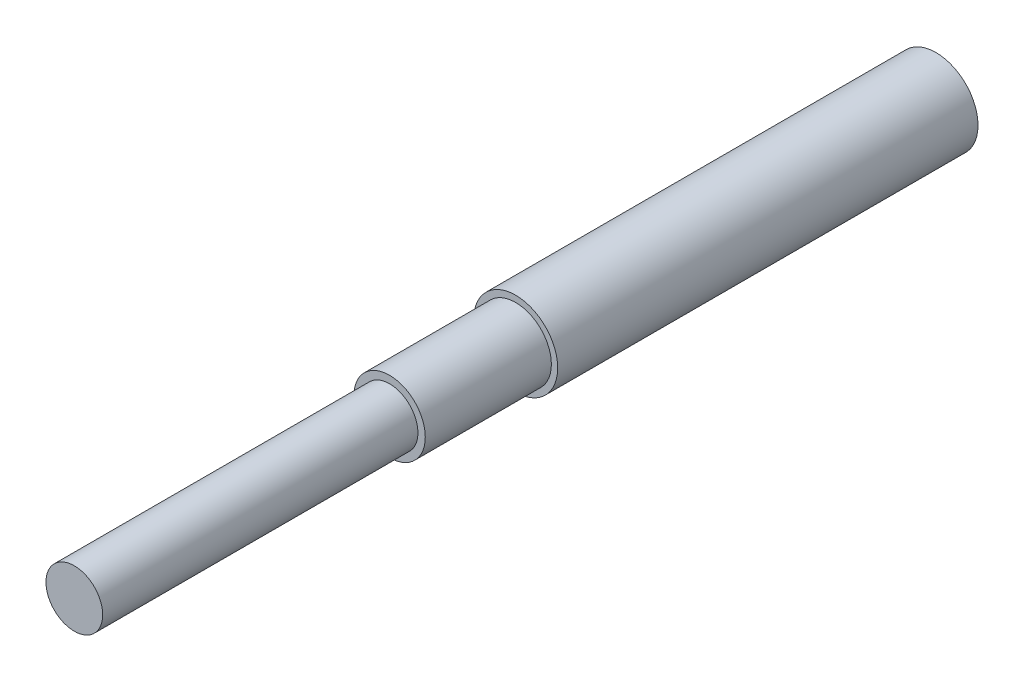
SolidWorks part; units mm, degrees
ref_plane "Plan de face" through (0, 0, 0) normal (0, 0, 1) x (1, 0, 0)
ref_plane "Plan de dessus" through (0, 0, 0) normal (0, 1, 0) x (1, 0, 0)
ref_plane "Plan de droite" through (0, 0, 0) normal (1, 0, 0) x (0, 0, -1)
sketch "Esquisse1" plane through (0, 0, 0) normal (0, 0, 1) x (1, 0, 0)
  circle A0 centre (0, 0) radius 2
  dimension "D1" = 4
extrude "Boss.-Extru.1" add sketch "Esquisse1" along normal blind 20
sketch "Esquisse8" plane through (0, 0, 20) normal (0, 0, 1) x (1, 0, 0)
  circle A0 centre (0, 0) radius 1.7
  dimension "D1" = 3.4
extrude "Boss.-Extru.2" add sketch "Esquisse8" along normal blind 6
sketch "Esquisse9" plane through (0, 0, 26) normal (0, 0, 1) x (1, 0, 0)
  circle A0 centre (0, 0) radius 1.35
  dimension "D1" = 2.7
extrude "Boss.-Extru.3" add sketch "Esquisse9" along normal blind 15
